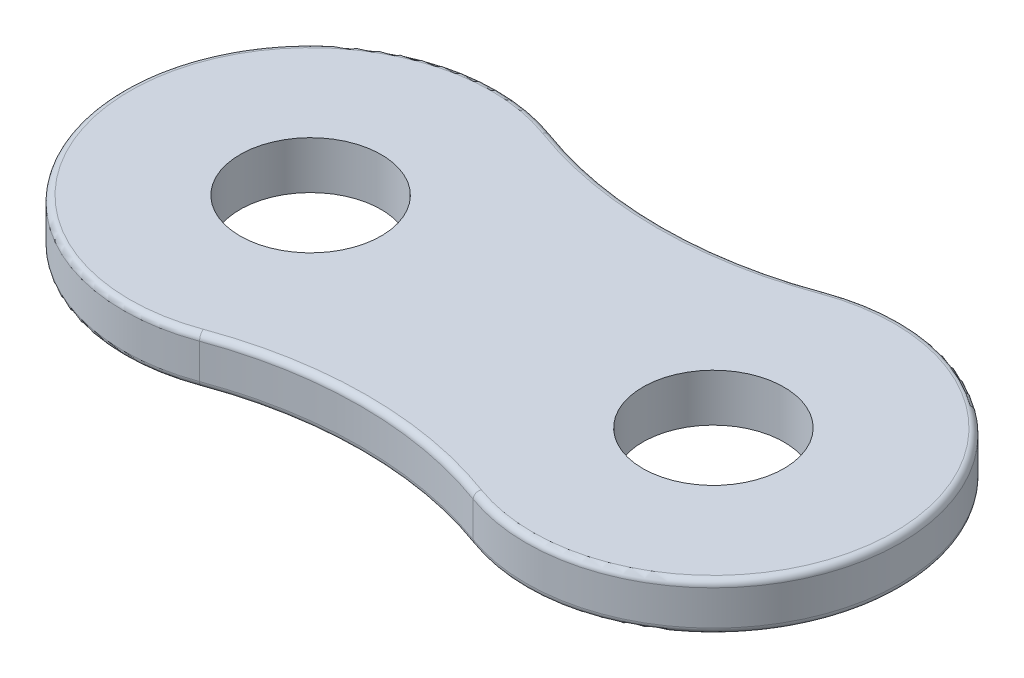
SolidWorks part; units mm, degrees
ref_plane "Płaszczyzna przednia" through (0, 0, 0) normal (0, 0, 1) x (1, 0, 0)
ref_plane "Płaszczyzna górna" through (0, 0, 0) normal (0, 1, 0) x (1, 0, 0)
ref_plane "Płaszczyzna prawa" through (0, 0, 0) normal (1, 0, 0) x (0, 0, -1)
sketch "Szkic1" plane through (0, 0, 0) normal (0, 1, 0) x (1, 0, 0)
  arc A0 (2.0361, 5.5375) -> (2.0361, -5.5375) centre (0, 0) ccw
  arc A1 (10.6639, -5.5375) -> (10.6639, 5.5375) centre (12.7, 0) ccw
  arc A2 (2.0361, 5.5375) -> (10.6639, 5.5375) centre (6.35, 17.2696) ccw
  arc A3 (10.6639, -5.5375) -> (2.0361, -5.5375) centre (6.35, -17.2696) ccw
  circle A4 centre (0, 0) radius 2.225
  circle A5 centre (12.7, 0) radius 2.225
  dimension "D2" = 11.8
  dimension "D3" = 4.45
  dimension "D4" = 25
  dimension "D1" = 12.7
extrude "Dodanie-wyciągnięcie1" add sketch "Szkic1" along normal blind 1.5
fillet "Zaokrąglenie1" radius 0.2 8 edges at (18.6, 0, 0) (6.35, 0, 4.7696) (-5.9, 0, 0) (18.6, 1.5, 0) (6.35, 1.5, 4.7696) (-5.9, 1.5, 0) (6.35, 0, -4.7696) (6.35, 1.5, -4.7696)
